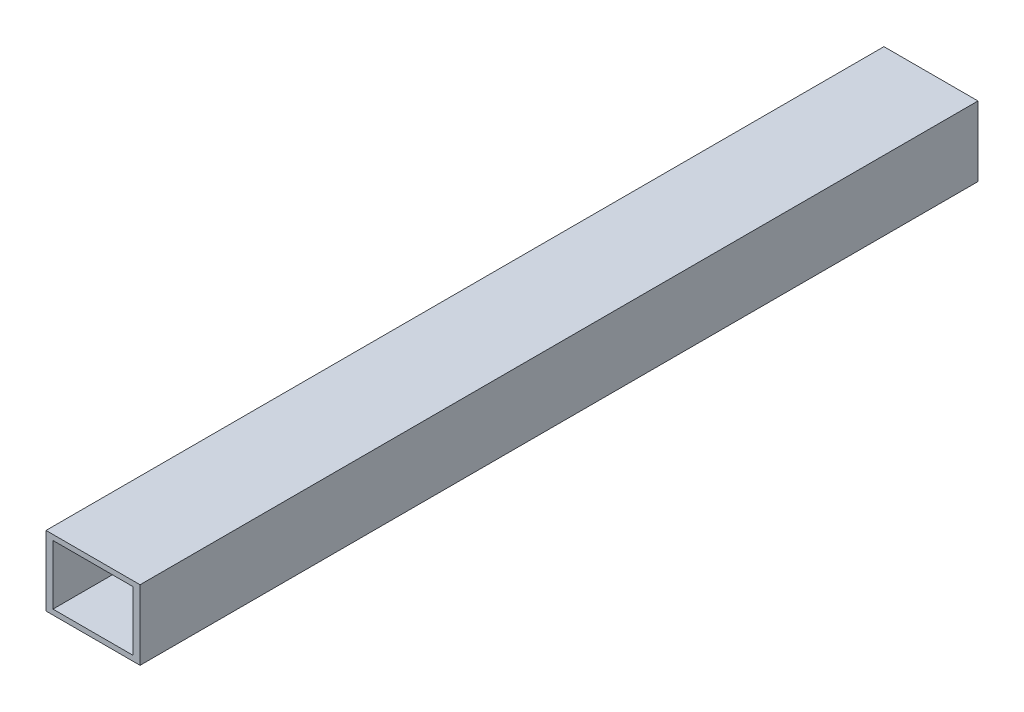
SolidWorks part; units mm, degrees
ref_plane "Front Plane" through (0, 0, 0) normal (0, 0, 1) x (1, 0, 0)
ref_plane "Top Plane" through (0, 0, 0) normal (0, 1, 0) x (1, 0, 0)
ref_plane "Right Plane" through (0, 0, 0) normal (1, 0, 0) x (0, 0, -1)
sketch "Sketch1" plane through (0, 0, 0) normal (0, 0, 1) x (1, 0, 0)
  line L1 (-34.2141, -25.4) -> (34.2141, -25.4)
  line L2 (-34.2141, -25.4) -> (-34.2141, 25.4)
  line L3 (-34.2141, 25.4) -> (34.2141, 25.4)
  line L4 (34.2141, -25.4) -> (34.2141, 25.4)
  line L5 (-34.2141, -25.4) -> (34.2141, 25.4) construction
  line L6 (-34.2141, 25.4) -> (34.2141, -25.4) construction
  line L7 (-29.1341, -21.6287) -> (29.1341, -21.6287)
  line L8 (-29.1341, -21.6287) -> (-29.1341, 21.6287)
  line L9 (-29.1341, 21.6287) -> (29.1341, 21.6287)
  line L10 (29.1341, -21.6287) -> (29.1341, 21.6287)
  line L11 (-29.1341, -21.6287) -> (29.1341, 21.6287) construction
  line L12 (-29.1341, 21.6287) -> (29.1341, -21.6287) construction
  point P0 (0, 0)
  point P6 (0, 0)
  dimension "D1" = 5.08
  dimension "D2" = 50.8
  dimension "D3" = 43.2574
  dimension "D4" = 68.4282
extrude "Boss-Extrude1" add sketch "Sketch1" along normal blind 609.6
